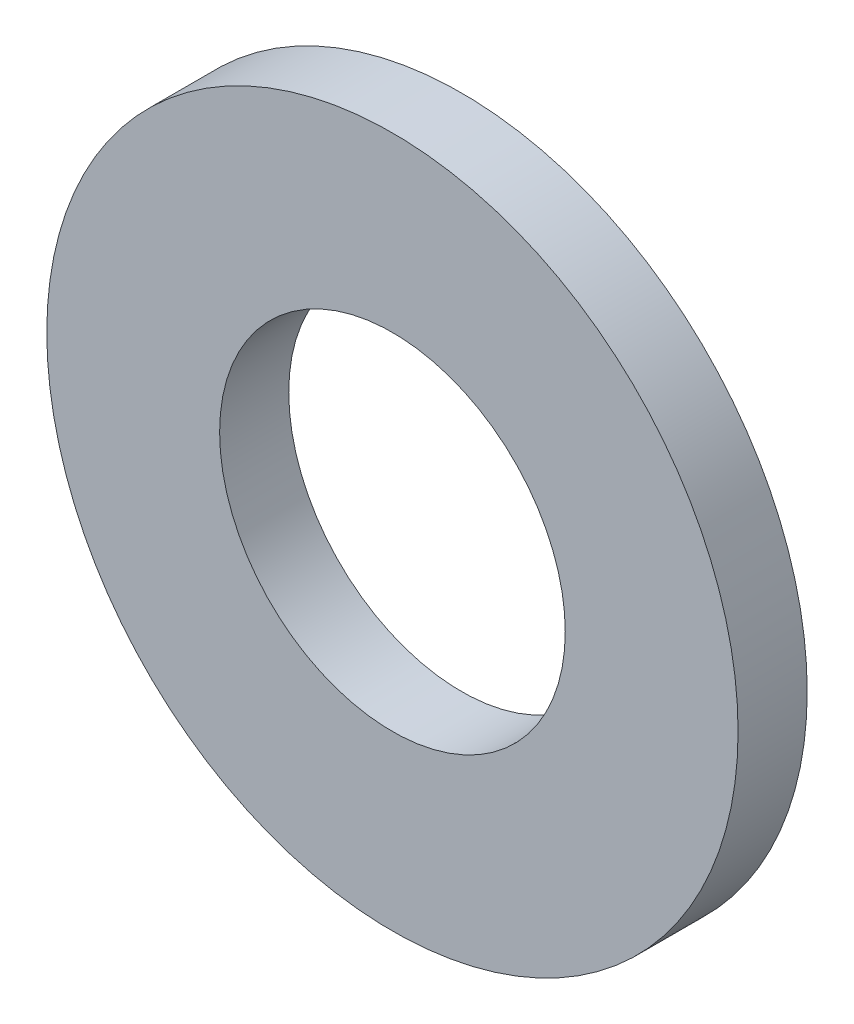
SolidWorks part; units mm, degrees
ref_plane "Front Plane" through (0, 0, 0) normal (0, 0, 1) x (1, 0, 0)
ref_plane "Top Plane" through (0, 0, 0) normal (0, 1, 0) x (1, 0, 0)
ref_plane "Right Plane" through (0, 0, 0) normal (1, 0, 0) x (0, 0, -1)
sketch "Sketch1" plane through (0, 0, 0) normal (0, 0, 1) x (1, 0, 0)
  circle A0 centre (0, 0) radius 2.5
  circle A1 centre (0, 0) radius 1.25
  dimension "D1" = 2.5
  dimension "D2" = 5
extrude "Boss-Extrude1" add sketch "Sketch1" along normal blind 0.5
